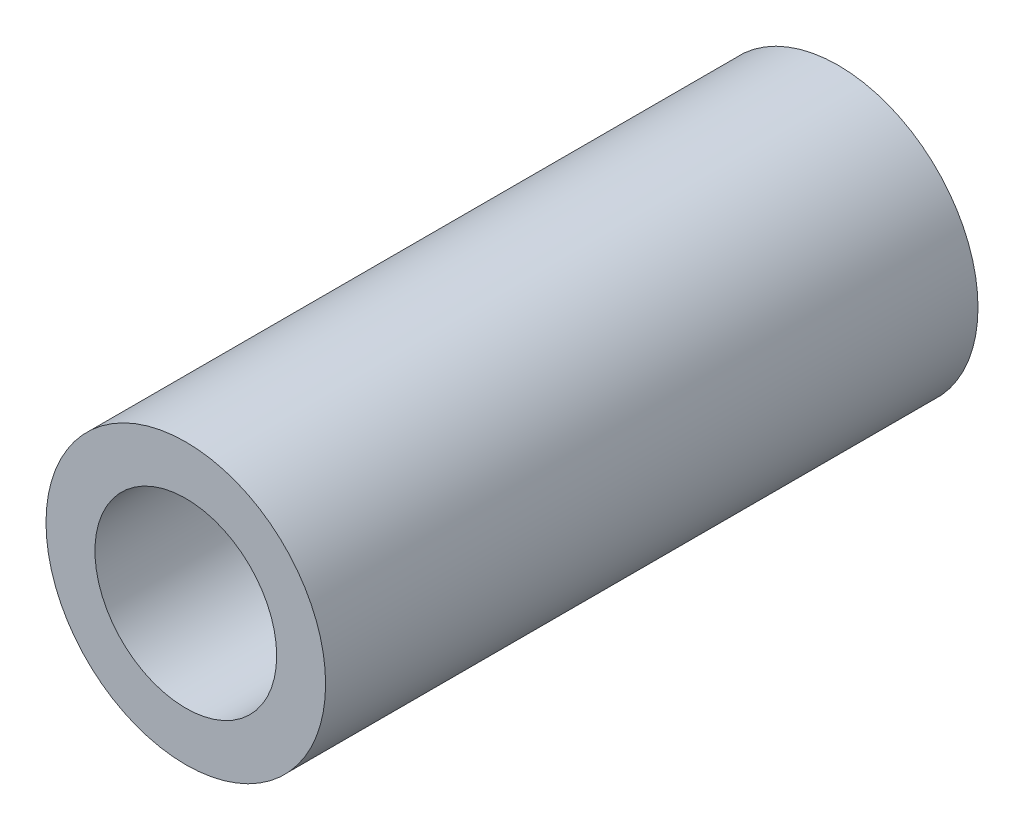
SolidWorks part; units mm, degrees
ref_plane "Plan de face" through (0, 0, 0) normal (1, 0, 0) x (0, 1, 0)
ref_plane "Plan de dessus" through (0, 0, 0) normal (0, 0, 1) x (0, 1, 0)
ref_plane "Plan de droite" through (0, 0, 0) normal (0, 1, 0) x (-1, 0, 0)
sketch "Esquisse1" plane through (0, 0, 0) normal (0, 0, 1) x (0, 1, 0)
  circle A0 centre (0, 0) radius 7.5
  dimension "D1" = 15
extrude "Boss.-Extru.1" add sketch "Esquisse1" along normal blind 35
sketch "Esquisse2" plane through (0, 0, 35) normal (0, 0, 1) x (1, 0, 0)
  circle A0 centre (0, 0) radius 4.875
  dimension "D1" = 9.75
extrude "Enlèv. mat.-Extru.1" cut sketch "Esquisse2" against normal blind 16
sketch "Esquisse3" plane through (0, 0, 0) normal (0, 0, -1) x (1, 0, 0)
  circle A0 centre (0, 0) radius 4.05
  dimension "D1" = 8.1
extrude "Enlèv. mat.-Extru.2" cut sketch "Esquisse3" against normal blind 16
sketch "Esquisse5" plane through (0, 0, 16) normal (0, 0, -1) x (1, 0, 0)
  line L0 (-2.822, 2.9049) -> (3.2005, 2.4818)
  arc A0 (-2.822, 2.9049) -> (3.2005, 2.4818) centre (0, 0) cw
  circle A1 centre (0, 0) radius 4.05 construction
  dimension "D1" = 2.7
extrude "Boss.-Extru.3" add sketch "Esquisse5" along normal blind 9
